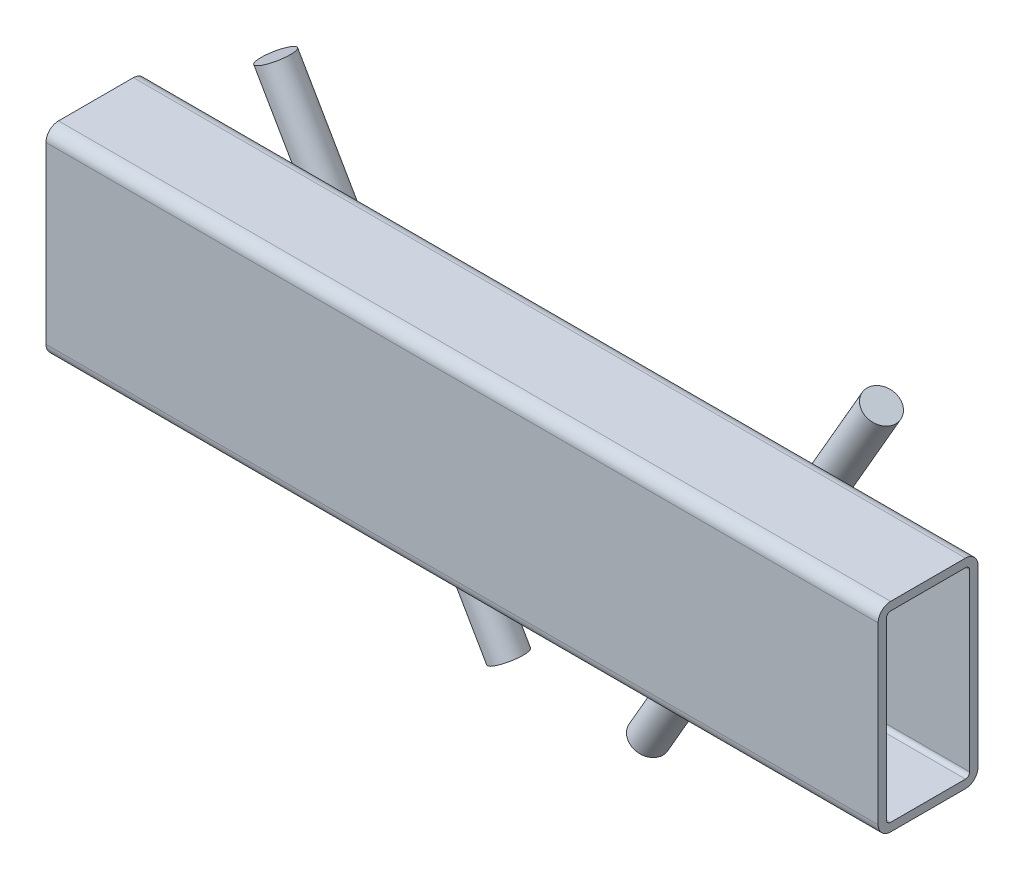
SolidWorks part; units mm, degrees
ref_plane "Спереди" through (0, 0, 0) normal (0, 0, 1) x (1, 0, 0)
ref_plane "Сверху" through (0, 0, 0) normal (0, 1, 0) x (1, 0, 0)
ref_plane "Справа" through (0, 0, 0) normal (1, 0, 0) x (0, 0, -1)
sketch "Эскиз1" plane through (0, 0, 0) normal (0, 1, 0) x (1, 0, 0)
  line L0 (-125, 0) -> (125, 0)
  point P4 (0, 0)
  dimension "D1" = 250
other "Труба axbxs гост8645-68 60 X 30 X 3(1)"
ref_plane "Плоскость1" through (-125, 0, 0) normal (1, 0, 0) x (0, 0, -1)
sketch "Sketch1" plane through (-125, 0, 0) normal (1, 0, 0) x (0, 0, -1)
  line L0 (-11.25, -27.5) -> (11.25, -27.5)
  line L1 (-12.5, -26.25) -> (-12.5, 26.25)
  line L2 (11.25, 27.5) -> (-11.25, 27.5)
  line L3 (12.5, 26.25) -> (12.5, -26.25)
  line L4 (-11.25, -30) -> (11.25, -30)
  line L5 (-15, -26.25) -> (-15, 26.25)
  line L6 (11.25, 30) -> (-11.25, 30)
  line L7 (15, 26.25) -> (15, -26.25)
  arc A0 (15, 26.25) -> (11.25, 30) centre (11.25, 26.25) ccw
  arc A1 (11.25, -30) -> (15, -26.25) centre (11.25, -26.25) ccw
  arc A2 (-15, -26.25) -> (-11.25, -30) centre (-11.25, -26.25) ccw
  arc A3 (-11.25, 30) -> (-15, 26.25) centre (-11.25, 26.25) ccw
  arc A4 (-11.25, 27.5) -> (-12.5, 26.25) centre (-11.25, 26.25) ccw
  arc A5 (12.5, 26.25) -> (11.25, 27.5) centre (11.25, 26.25) ccw
  arc A6 (11.25, -27.5) -> (12.5, -26.25) centre (11.25, -26.25) ccw
  arc A7 (-12.5, -26.25) -> (-11.25, -27.5) centre (-11.25, -26.25) ccw
  point P0 (0, 30)
  point P1 (15, 0)
  point P2 (0, -30)
  point P3 (-15, 0)
  point P4 (-15, 30)
  point P5 (15, 30)
  point P6 (15, -30)
  point P7 (-15, -30)
  point P8 (0, 0)
  point P33 (0, 0)
  dimension "D1" = 3.75
  dimension "Thickness" = 2.5
  dimension "V_leg" = 60
  dimension "H_leg" = 30
ref_plane "Плоскость2" through (0, 0, -20) normal (0, 0, -1) x (-1, 0, 0)
sketch "Эскиз3" plane through (0, 0, -20) normal (0, 0, -1) x (-1, 0, 0)
  line L0 (21, -73) -> (91, 48.2436)
  line L2 (0, 0) -> (0, 111.8236) construction
  line L4 (-125, -30) -> (125, -30) construction
  dimension "D1" = 21
  dimension "D2" = 91
  dimension "D3" = 140
  dimension "D4" = 43
ref_plane "Плоскость3" through (-21, -73, -20) normal (-0.5, 0.866, 0) x (0.866, 0.5, 0)
sketch "Эскиз4" plane through (-21, -73, -20) normal (-0.5, 0.866, 0) x (0.866, 0.5, 0)
  circle A0 centre (0, 0) radius 5
  dimension "D1" = 10
sweep "По траектории1" add profiles "Эскиз4" path "Эскиз3"
mirror "Зеркальное отражение1" about plane through (0, 0, 0) normal (1, 0, 0) of bodies 104
sketch "Эскиз6" plane through (0, 0, -15) normal (0, 0, -1) x (-1, 0, 0)
  line L0 (0, 0) -> (0, 52.566) construction
  line L1 (-125, -26.25) -> (-125, 26.25) construction
  line L5 (-125, 30) -> (125, 30) construction
  circle A0 centre (-110, 12) radius 5 construction
  circle A1 centre (110, 12) radius 5 construction
  dimension "D2" = 18
  dimension "D3" = 10
  dimension "D1" = 15
